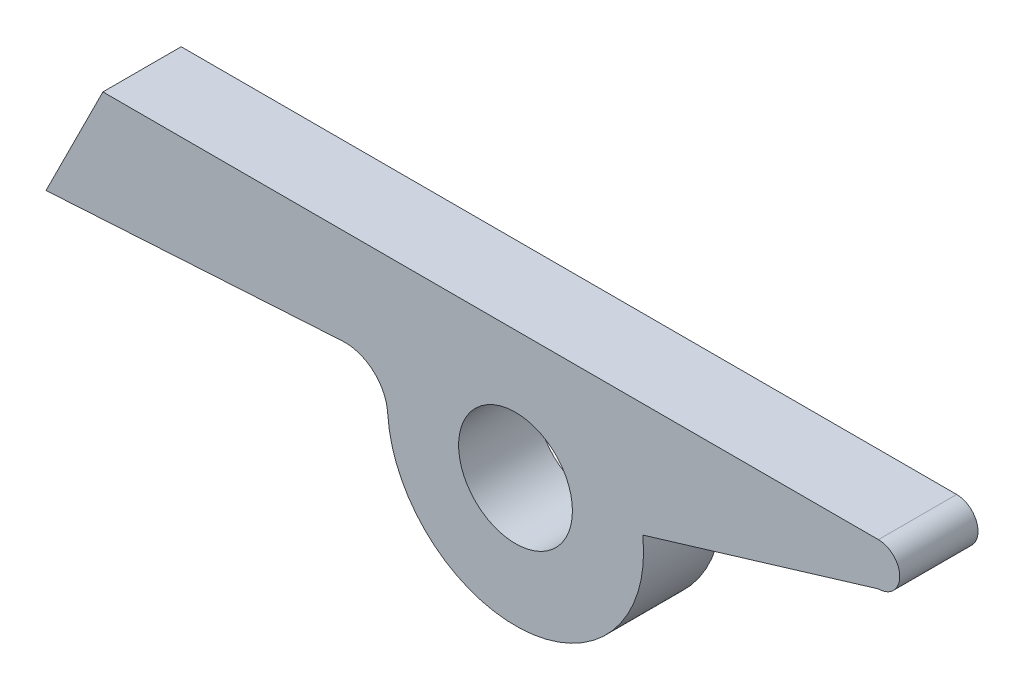
SolidWorks part; units mm, degrees
ref_plane "Piano frontale" through (0, 0, 0) normal (0, 0, 1) x (1, 0, 0)
ref_plane "Piano superiore" through (0, 0, 0) normal (0, 1, 0) x (1, 0, 0)
ref_plane "Piano destro" through (0, 0, 0) normal (1, 0, 0) x (0, 0, -1)
sketch "Schizzo1" plane through (0, 0, 0) normal (0, 0, 1) x (1, 0, 0)
  line L0 (-27.25, 0) -> (27.25, 0)
  line L1 (-27.25, 0) -> (-31.25, -8)
  line L2 (-31.25, -8) -> (-10.4103, -6.7454)
  line L3 (10.6914, -8) -> (27.25, -3)
  circle A0 centre (1.7472, -9) radius 4
  arc A1 (-7.2357, -9.555) -> (10.6914, -8) centre (1.7472, -9) ccw
  arc A2 (-7.2357, -9.555) -> (-10.4103, -6.7454) centre (-10.23, -9.74) ccw
  arc A3 (27.25, -3) -> (27.25, 0) centre (27.25, -1.5) ccw
  point P9 (25.756, -4.2643)
  point P10 (27.25, -3)
  point P11 (0, 0)
  dimension "D2" = 8
  dimension "D3" = 18
  dimension "D7" = 6
  dimension "D10" = 3
  dimension "D1" = 54.5
  dimension "D4" = 4
  dimension "D5" = 9
  dimension "D6" = 8
  dimension "D8" = 1.74
  dimension "D9" = 21.02
extrude "Estrusione-Estrusione1" add sketch "Schizzo1" along normal blind 5.5
